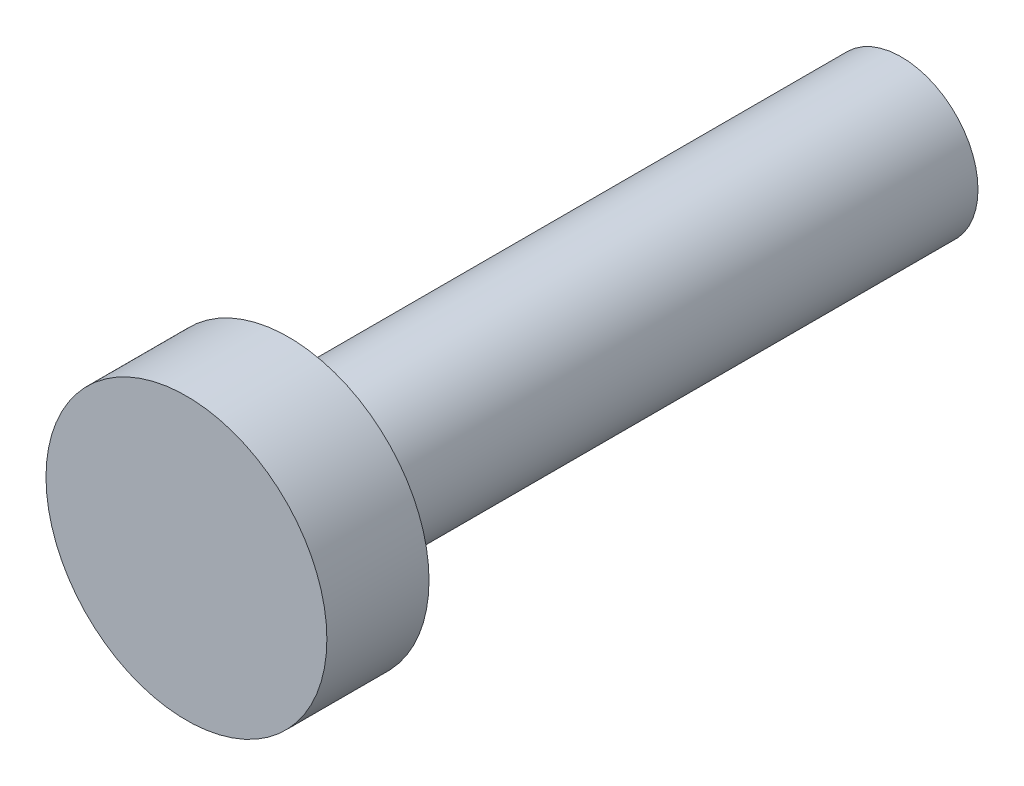
SolidWorks part; units mm, degrees
ref_plane "前视基准面" through (0, 0, 0) normal (0, 0, 1) x (1, 0, 0)
ref_plane "上视基准面" through (0, 0, 0) normal (0, 1, 0) x (1, 0, 0)
ref_plane "右视基准面" through (0, 0, 0) normal (1, 0, 0) x (0, 0, -1)
sketch "草图1" plane through (0, 0, 0) normal (0, 0, 1) x (1, 0, 0)
  circle A0 centre (0, 0) radius 1.5
  dimension "D1" = 3
extrude "M3螺杆_牙型简化" add sketch "草图1" along normal blind 12 from offset 12
sketch "草图2" plane through (0, 0, 0) normal (0, 0, 1) x (1, 0, 0)
  circle A0 centre (0, 0) radius 2.75
  dimension "D1" = 5.5
extrude "圆柱头_直径5.5" add sketch "草图2" along normal blind 2
